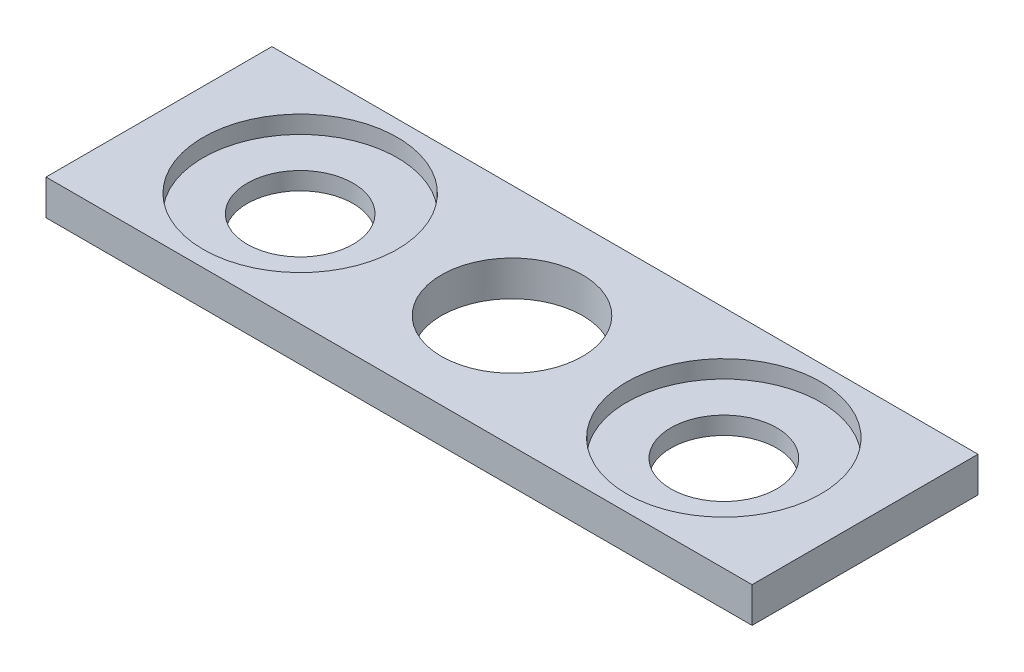
SolidWorks part; units mm, degrees
ref_plane "Front Plane" through (0, 0, 0) normal (0, 0, 1) x (1, 0, 0)
ref_plane "Top Plane" through (0, 0, 0) normal (0, 1, 0) x (1, 0, 0)
ref_plane "Right Plane" through (0, 0, 0) normal (1, 0, 0) x (0, 0, -1)
sketch "Sketch1" plane through (0, 0, 0) normal (0, 1, 0) x (1, 0, 0)
  line L0 (31.75, 0) -> (31.75, 20.32) construction
  line L1 (0, 0) -> (63.5, 0)
  line L2 (0, 0) -> (0, 20.32)
  line L3 (0, 20.32) -> (63.5, 20.32)
  line L4 (63.5, 0) -> (63.5, 20.32)
  circle A0 centre (12.7, 10.16) radius 4.7625
  circle A1 centre (50.8, 10.16) radius 4.7625
  dimension "D1" = 9.525
  dimension "D2" = 9.525
  dimension "D3" = 38.1
  dimension "D4" = 63.5
  dimension "D5" = 20.32
  dimension "D6" = 10.16
  dimension "D7" = 19.05
extrude "Boss-Extrude1" add sketch "Sketch1" along normal blind 3.175
sketch "Sketch2" plane through (0, 3.175, 0) normal (0, 1, 0) x (1, 0, 0)
  line L0 (31.75, 0) -> (31.75, 20.32) construction
  line L1 (0, 0) -> (63.5, 0) construction
  line L2 (63.5, 20.32) -> (0, 20.32) construction
  circle A0 centre (31.75, 10.16) radius 6.35
  point P9 (31.75, 10.16)
  dimension "D1" = 12.7
extrude "Cut-Extrude1" cut sketch "Sketch2" against normal blind 6.35
sketch "Sketch3" plane through (0, 3.175, 0) normal (0, 1, 0) x (1, 0, 0)
  circle A0 centre (12.7, 10.16) radius 8.7312
  circle A1 centre (50.8, 10.16) radius 8.7312
  dimension "D1" = 17.4625
  dimension "D2" = 17.4625
extrude "Cut-Extrude2" cut sketch "Sketch3" against normal blind 1.5875
